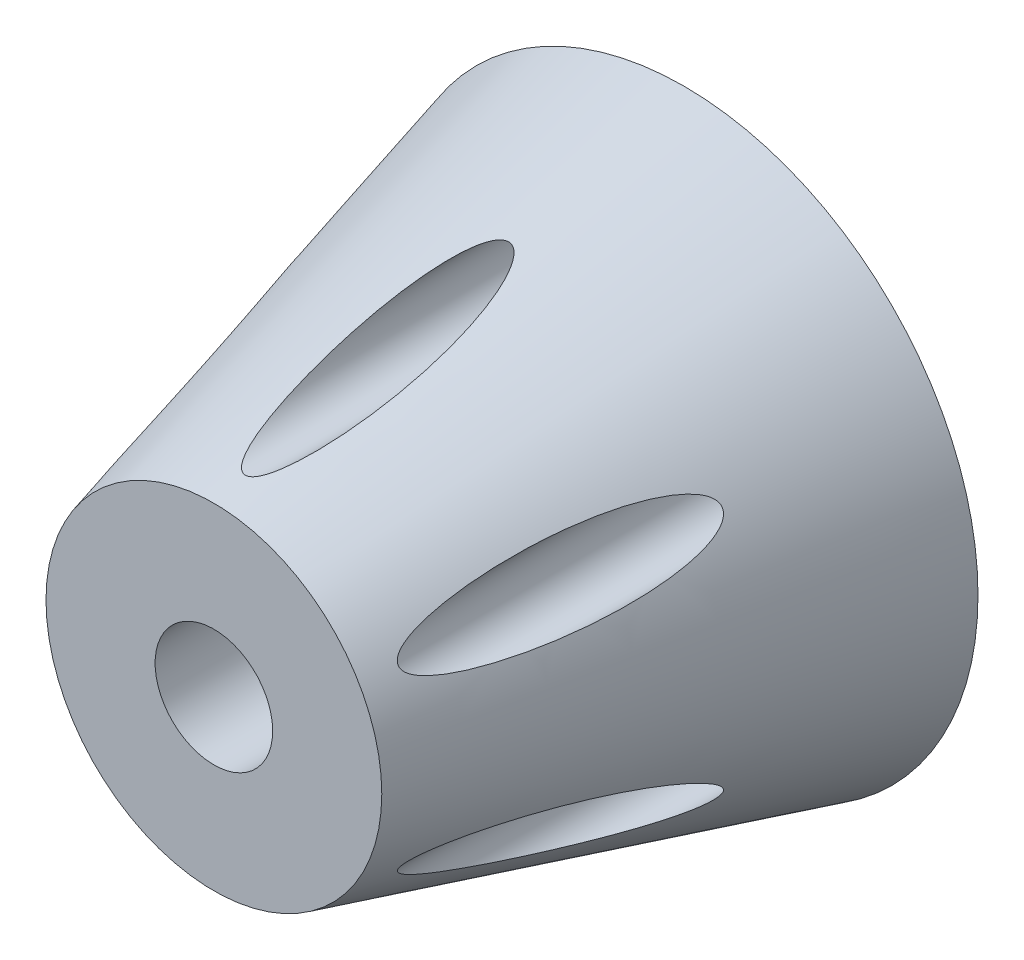
SolidWorks part; units mm, degrees
ref_plane "Front Plane" through (0, 0, 0) normal (0, 0, 1) x (1, 0, 0)
ref_plane "Top Plane" through (0, 0, 0) normal (0, 1, 0) x (1, 0, 0)
ref_plane "Right Plane" through (0, 0, 0) normal (1, 0, 0) x (0, 0, -1)
sketch "Sketch2" plane through (0, 0, 0) normal (0, 0, 1) x (1, 0, 0)
  circle A0 centre (0, 0) radius 125
  dimension "D1" = 250
extrude "Boss-Extrude1" add sketch "Sketch2" along normal blind 200 draft 15
sketch "Sketch3" plane through (0, 0, 200) normal (0, 0, 1) x (1, 0, 0)
  circle A0 centre (0, 0) radius 25
  dimension "D1" = 50
extrude "Cut-Extrude1" cut sketch "Sketch3" against normal through all
sketch "Sketch4" plane through (0, 0, 0) normal (0, 0, -1) x (-1, 0, 0)
  circle A0 centre (0, 0) radius 90 construction
  circle A1 centre (0, 90) radius 5
  circle A2 centre (77.9423, 45) radius 5
  circle A3 centre (77.9423, -45) radius 5
  circle A4 centre (0, -90) radius 5
  circle A5 centre (-77.9423, -45) radius 5
  circle A6 centre (-77.9423, 45) radius 5
  point P17 (0, 0)
  dimension "D1" = 10
  dimension "D2" = 180
  dimension "D3" = 6
extrude "Cut-Extrude2" cut sketch "Sketch4" against normal through all
sketch "Sketch5" plane through (0, 0, 0) normal (0, 0, -1) x (-1, 0, 0)
  circle A0 centre (0, 0) radius 90 construction
  circle A1 centre (0, 90) radius 15
  circle A2 centre (77.9423, 45) radius 15
  circle A3 centre (77.9423, -45) radius 15
  circle A4 centre (0, -90) radius 15
  circle A5 centre (-77.9423, -45) radius 15
  circle A6 centre (-77.9423, 45) radius 15
  point P18 (0, 0)
  dimension "D1" = 30
  dimension "D2" = 6
extrude "Cut-Extrude3" cut sketch "Sketch5" against normal through all from offset 50
